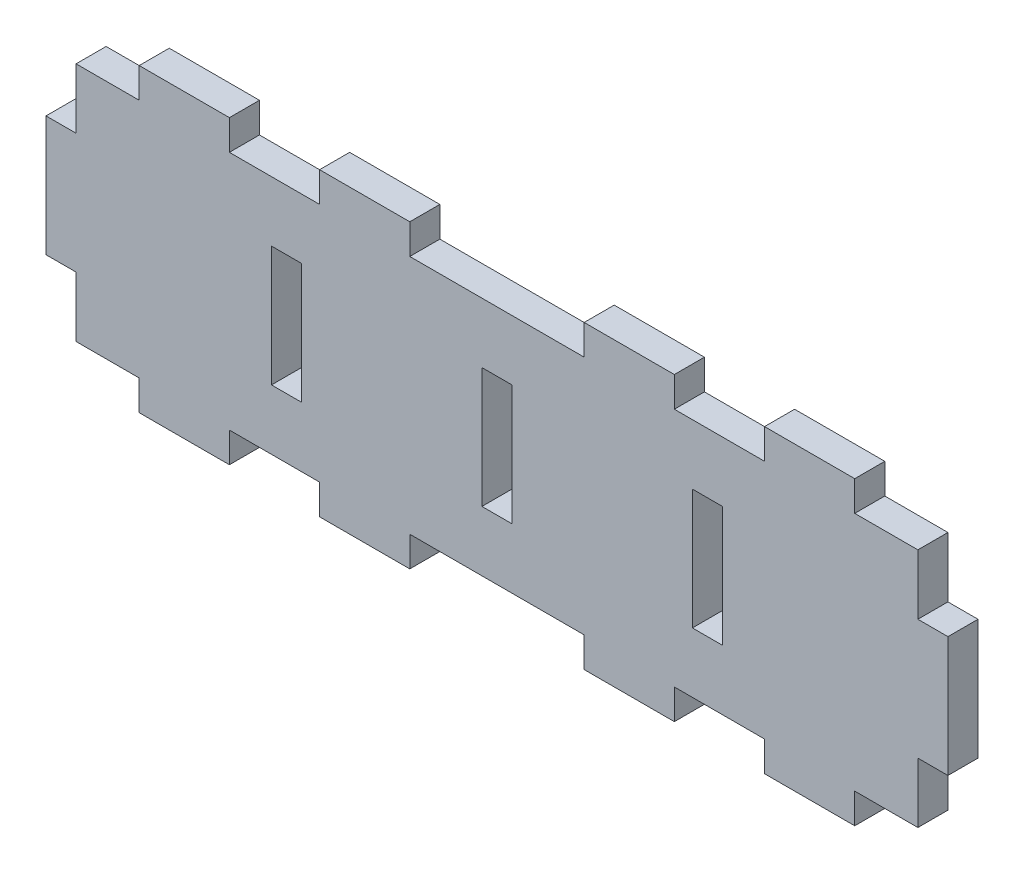
SolidWorks part; units mm, degrees
ref_plane "Front Plane" through (0, 0, 0) normal (0, 0, 1) x (1, 0, 0)
ref_plane "Top Plane" through (0, 0, 0) normal (0, 1, 0) x (1, 0, 0)
ref_plane "Right Plane" through (0, 0, 0) normal (1, 0, 0) x (0, 0, -1)
sketch "Sketch1" plane through (0, 0, 0) normal (0, 0, 1) x (1, 0, 0)
  line L0 (0, 0) -> (0, 13.6771) construction
  line L1 (-70, 20) -> (-59.5, 20)
  line L2 (-75, 10) -> (-75, -10)
  line L3 (-70, -20) -> (-59.5, -20)
  line L4 (75, 10) -> (75, -10)
  line L5 (-70, 23.3333) -> (70, -23.3333) construction
  line L6 (-70, -23.3333) -> (70, 23.3333) construction
  line L9 (-75, 10) -> (-70, 10)
  line L11 (-75, 10) -> (-70, 10)
  line L12 (-75, 10) -> (-75, -10)
  line L13 (-75, -10) -> (-70, -10)
  line L15 (-75, -10) -> (-70, -10)
  line L19 (0, 0) -> (14.851, 0) construction
  line L20 (14.5, 20) -> (14.5, 25)
  line L22 (-59.5, 20) -> (-59.5, 25)
  line L23 (-59.5, 25) -> (-44.5, 25)
  line L24 (-44.5, 20) -> (-44.5, 25)
  line L26 (-29.5, 20) -> (-29.5, 25)
  line L27 (-29.5, 25) -> (-14.5, 25)
  line L28 (-14.5, 20) -> (-14.5, 25)
  line L29 (29.5, 20) -> (29.5, 25)
  line L30 (29.5, 25) -> (14.5, 25)
  line L31 (44.5, 20) -> (44.5, 25)
  line L32 (59.5, 20) -> (59.5, 25)
  line L33 (59.5, 25) -> (44.5, 25)
  line L34 (59.5, -20) -> (59.5, -25)
  line L35 (44.5, -20) -> (44.5, -25)
  line L36 (59.5, -25) -> (44.5, -25)
  line L37 (29.5, -20) -> (29.5, -25)
  line L38 (14.5, -20) -> (14.5, -25)
  line L39 (29.5, -25) -> (14.5, -25)
  line L40 (-14.5, -20) -> (-14.5, -25)
  line L41 (-29.5, -20) -> (-29.5, -25)
  line L42 (-29.5, -25) -> (-14.5, -25)
  line L43 (-44.5, -20) -> (-44.5, -25)
  line L44 (-59.5, -25) -> (-44.5, -25)
  line L45 (-59.5, -20) -> (-59.5, -25)
  line L46 (-44.5, 20) -> (-29.5, 20)
  line L47 (-14.5, 20) -> (14.5, 20)
  line L48 (29.5, 20) -> (44.5, 20)
  line L49 (59.5, 20) -> (70, 20)
  line L50 (59.5, -20) -> (70, -20)
  line L51 (29.5, -20) -> (44.5, -20)
  line L52 (-14.5, -20) -> (14.5, -20)
  line L53 (-44.5, -20) -> (-29.5, -20)
  line L54 (75, -10) -> (70, -10)
  line L55 (75, 10) -> (75, -10)
  line L56 (75, 10) -> (70, 10)
  line L57 (70, 20) -> (70, 10)
  line L58 (70, -20) -> (70, -10)
  line L59 (-70, -20) -> (-70, -10)
  line L60 (-70, 10) -> (-70, 20)
  line L73 (37.5, -10) -> (37.5, 10)
  line L74 (37.5, 10) -> (32.5, 10)
  line L75 (32.5, 10) -> (32.5, -10)
  line L76 (32.5, -10) -> (37.5, -10)
  line L77 (2.5, -10) -> (2.5, 10)
  line L78 (2.5, 10) -> (-2.5, 10)
  line L79 (-2.5, 10) -> (-2.5, -10)
  line L80 (-2.5, -10) -> (2.5, -10)
  line L81 (-32.5, -10) -> (-32.5, 10)
  line L82 (-32.5, 10) -> (-37.5, 10)
  line L83 (-37.5, 10) -> (-37.5, -10)
  line L84 (-37.5, -10) -> (-32.5, -10)
  point P0 (0, 0)
  point P1 (-75, 0)
  dimension "D1" = 15
  dimension "D2" = 15
  dimension "D3" = 14.5
  dimension "D4" = 150
  dimension "D5" = 20
  dimension "D6" = 15
  dimension "D7" = 25
  dimension "D8" = 5
  dimension "D9" = 5
  dimension "D10" = 5
extrude "Boss-Extrude1" add sketch "Sketch1" along normal blind 5 contours L60 L9 L2 L13 L59 L3 L45 L44 L43 L53 L41 L42 L40 L52 L38 L39 L37 L51 L35 L36 L34 L50 L58 L54 L4 L56 L57 L49 L32 L33 L31 L48 L29 L30 L20 L47 L28 L27 L26 L46 L24 L23 L22 L1
